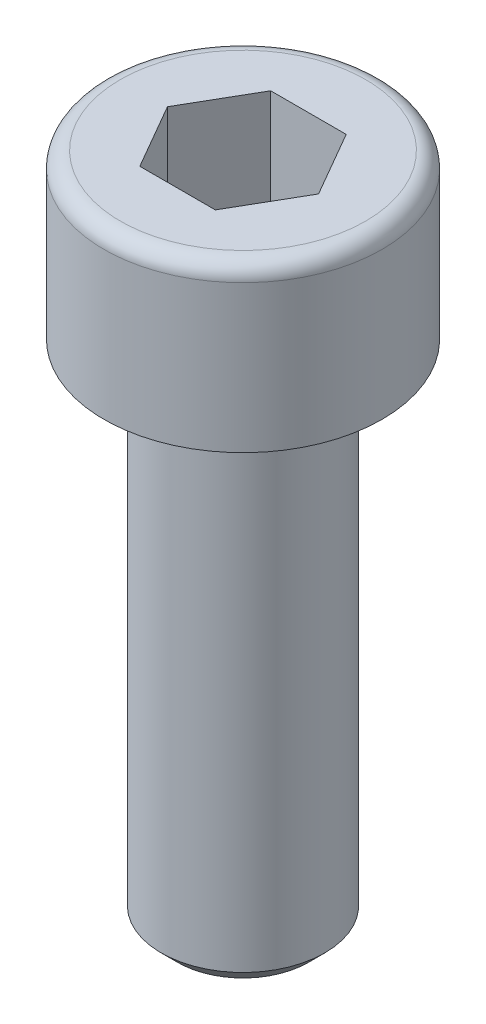
SolidWorks part; units mm, degrees
ref_plane "Спереди" through (0, 0, 0) normal (0, 0, 1) x (1, 0, 0)
ref_plane "Сверху" through (0, 0, 0) normal (0, 1, 0) x (1, 0, 0)
ref_plane "Справа" through (0, 0, 0) normal (1, 0, 0) x (0, 0, -1)
other "Configuration Table"
sketch "Эскиз1" plane through (0, 0, 0) normal (0, 0, 1) x (1, 0, 0)
  line L0 (0, -169.0155) -> (0, 8281.7599) construction
  line L1 (0, 0) -> (2.5, 0)
  line L2 (2.5, 0) -> (2.5, 15)
  line L3 (3, 15.5) -> (4.25, 15.5)
  line L4 (4.25, 15.5) -> (4.25, 20)
  line L5 (3.75, 20.5) -> (0, 20.5)
  line L6 (0, 20.5) -> (0, 0)
  arc A0 (3, 15.5) -> (2.5, 15) centre (3, 15) ccw
  arc A1 (3.75, 20.5) -> (4.25, 20) centre (3.75, 20) cw
  dimension "D5" = 0.5
  dimension "D1" = 5
  dimension "D2" = 8.5
  dimension "D3" = 5
  dimension "D4" = 20.5
revolve "Повернуть1" add sketch "Эскиз1" angle 360 about L0
chamfer "Фаска1" distance 0.5 angle 45 1 edges at (2.5, 0, 0)
sketch "Эскиз2" plane through (0, 20.5, 0) normal (0, 1, 0) x (1, 0, 0)
  line L1 (2.3094, 0) -> (1.1547, 2)
  line L2 (1.1547, 2) -> (-1.1547, 2)
  line L3 (-1.1547, 2) -> (-2.3094, 0)
  line L4 (-2.3094, 0) -> (-1.1547, -2)
  line L5 (-1.1547, -2) -> (1.1547, -2)
  line L6 (1.1547, -2) -> (2.3094, 0)
  circle A0 centre (0, 0) radius 2 construction
  dimension "D1" = 4
extrude "Вырез-Вытянуть1" cut sketch "Эскиз2" against normal blind 3
